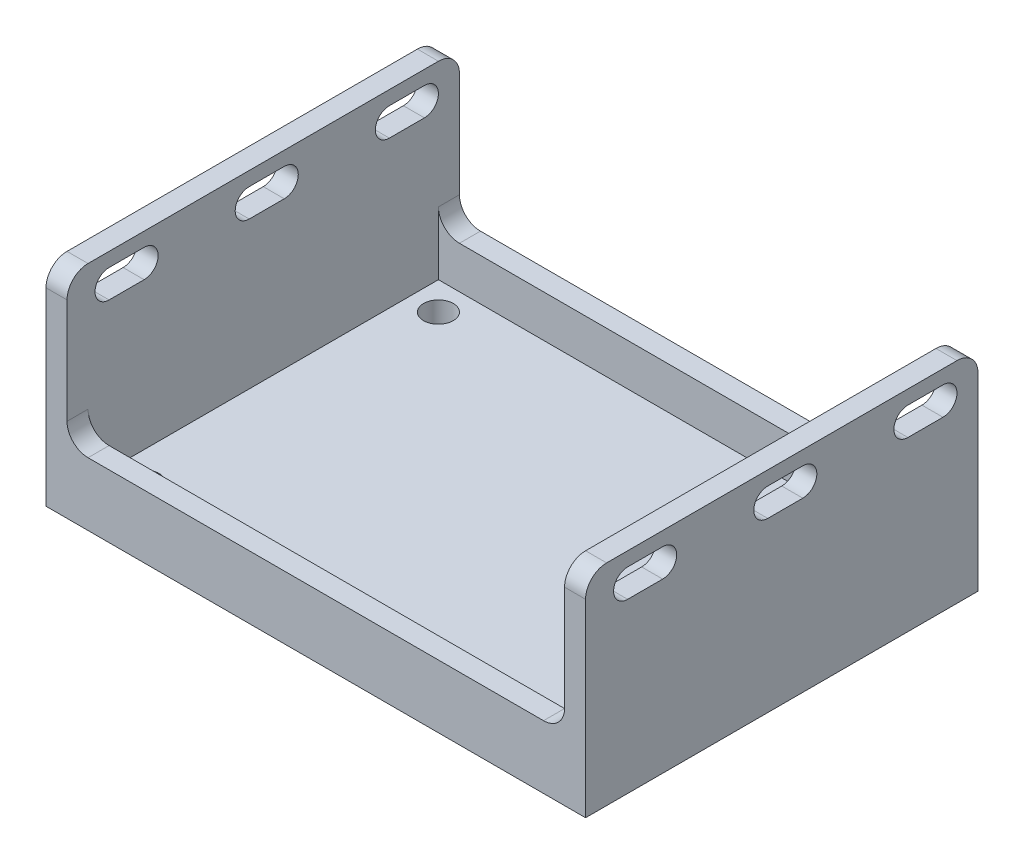
SolidWorks part; units mm, degrees
ref_plane "Front Plane" through (0, 0, 0) normal (0, 0, 1) x (1, 0, 0)
ref_plane "Top Plane" through (0, 0, 0) normal (0, 1, 0) x (1, 0, 0)
ref_plane "Right Plane" through (0, 0, 0) normal (1, 0, 0) x (0, 0, -1)
sketch "Sketch1" plane through (0, 0, 0) normal (0, 1, 0) x (1, 0, 0)
  line L1 (35.5, 25) -> (-35.5, 25)
  line L2 (35.5, 25) -> (35.5, -25)
  line L3 (35.5, -25) -> (-35.5, -25)
  line L4 (-35.5, 25) -> (-35.5, -25)
  line L5 (0, -25) -> (0, 25) construction
  line L6 (35.5, 0) -> (-35.5, 0) construction
  line L7 (31.5, 21) -> (-31.5, 21) construction
  line L8 (31.5, 21) -> (31.5, -21) construction
  line L9 (31.5, -21) -> (-31.5, -21) construction
  line L10 (-31.5, 21) -> (-31.5, -21) construction
  line L11 (0, -21) -> (0, 21) construction
  line L12 (31.5, 0) -> (-31.5, 0) construction
  circle A0 centre (-31.5, 21) radius 2.125
  circle A1 centre (31.5, 21) radius 2.125
  circle A2 centre (31.5, -21) radius 2.125
  circle A3 centre (-31.5, -21) radius 2.125
  point P0 (0, 0)
  point P4 (0, 0)
  dimension "D5" = 4.25
  dimension "D1" = 50
  dimension "D2" = 71
  dimension "D3" = 42
  dimension "D4" = 63
extrude "Boss-Extrude1" add sketch "Sketch1" along normal blind 3
sketch "Sketch2" plane through (0, 0, 0) normal (0, 1, 0) x (1, 0, 0)
  line L8 (-38.5, 28) -> (-38.5, -28)
  line L9 (-38.5, -28) -> (38.5, -28)
  line L10 (38.5, -28) -> (38.5, 28)
  line L11 (38.5, 28) -> (-38.5, 28)
  line L12 (-38.5, 28) -> (-38.5, -28)
  line L13 (-38.5, -28) -> (38.5, -28)
  line L14 (38.5, -28) -> (38.5, 28)
  line L15 (38.5, 28) -> (-38.5, 28)
  line L16 (-35.5, 25) -> (-35.5, -25)
  line L17 (-35.5, -25) -> (35.5, -25)
  line L18 (35.5, -25) -> (35.5, 25)
  line L19 (35.5, 25) -> (-35.5, 25)
  line L20 (-35.5, 25) -> (-35.5, -25)
  line L21 (-35.5, -25) -> (35.5, -25)
  line L22 (35.5, -25) -> (35.5, 25)
  line L23 (35.5, 25) -> (-35.5, 25)
  dimension "D1" = 3
  dimension "D2" = 0
extrude "Boss-Extrude2" add sketch "Sketch2" along normal blind 30
sketch "Sketch3" plane through (0, 0, -28) normal (0, 0, -1) x (-1, 0, 0)
  line L1 (-38.5, 30) -> (-38.5, 0) construction
  line L2 (-35.5, 39) -> (35.5, 39)
  line L3 (-35.5, 39) -> (-35.5, 9)
  line L4 (-35.5, 9) -> (35.5, 9)
  line L5 (35.5, 39) -> (35.5, 9)
  line L6 (38.5, 30) -> (38.5, 0) construction
  dimension "D1" = 9
  dimension "D2" = 3
  dimension "D3" = 3
  dimension "D4" = 30
extrude "Cut-Extrude1" cut sketch "Sketch3" against normal through all
sketch "Sketch4" plane through (-38.5, 0, 0) normal (-1, 0, 0) x (0, 0, 1)
  line L0 (-20.5, 26) -> (-20.5, 30) construction
  line L1 (-28, 30) -> (28, 30) construction
  line L2 (-18, 26) -> (-23, 26) construction
  line L3 (-18, 24) -> (-23, 24)
  line L4 (-18, 28) -> (-23, 28)
  line L5 (-23, 26) -> (-28, 26) construction
  line L6 (-28, 30) -> (-28, 0) construction
  line L7 (2, 28) -> (-3, 28)
  line L8 (2, 24) -> (-3, 24)
  line L9 (2, 26) -> (-3, 26) construction
  line L10 (22, 28) -> (17, 28)
  line L11 (22, 24) -> (17, 24)
  line L12 (22, 26) -> (17, 26) construction
  arc A0 (-18, 24) -> (-18, 28) centre (-18, 26) ccw
  arc A1 (-23, 28) -> (-23, 24) centre (-23, 26) ccw
  arc A2 (2, 24) -> (2, 28) centre (2, 26) ccw
  arc A3 (-3, 28) -> (-3, 24) centre (-3, 26) ccw
  arc A4 (22, 24) -> (22, 28) centre (22, 26) ccw
  arc A5 (17, 28) -> (17, 24) centre (17, 26) ccw
  point P7 (-20.5, 26)
  point P20 (-0.5, 26)
  point P27 (19.5, 26)
  dimension "D3" = 2
  dimension "D1" = 5
  dimension "D2" = 5
  dimension "D4" = 4
  dimension "D5" = 3
extrude "Cut-Extrude2" cut sketch "Sketch4" against normal through all
fillet "Fillet1" radius 3 8 edges at (-37, 30, 28) (-37, 30, -28) (37, 30, 28) (37, 30, -28) (-35.5, 9, -26.5) (-35.5, 9, 26.5) (35.5, 9, 26.5) (35.5, 9, -26.5)
